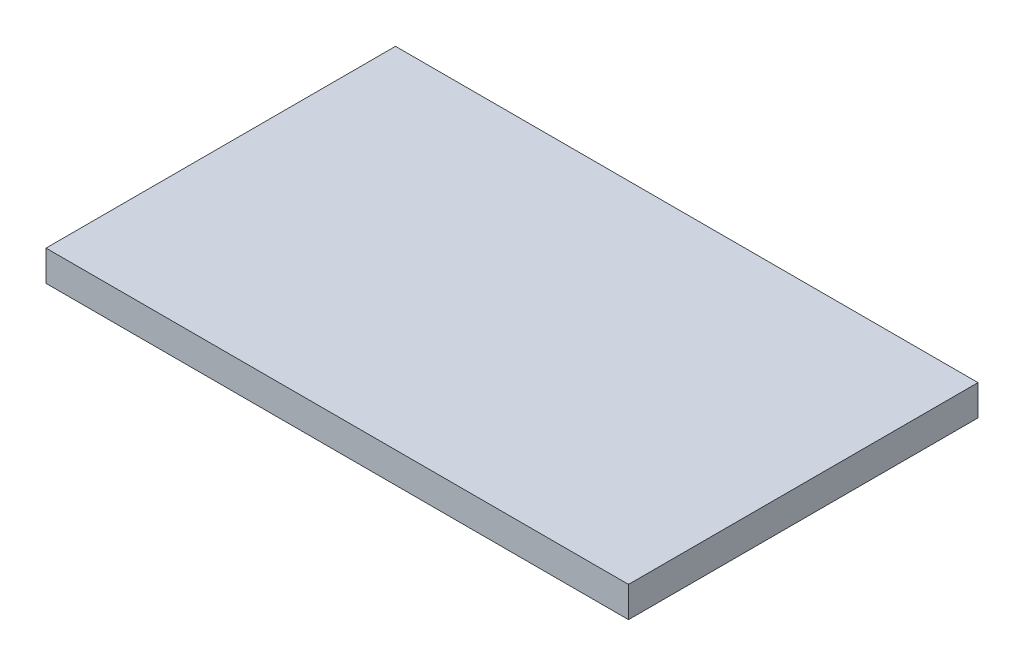
SolidWorks part; units mm, degrees
ref_plane "Front" through (0, 0, 0) normal (0, 0, 1) x (1, 0, 0)
ref_plane "Top" through (0, 0, 0) normal (0, 1, 0) x (1, 0, 0)
ref_plane "Right" through (0, 0, 0) normal (1, 0, 0) x (0, 0, -1)
sketch "Sketch1" plane through (0, 0, 0) normal (0, 1, 0) x (1, 0, 0)
  line L1 (0, 0) -> (-38.1, 0)
  line L2 (0, 0) -> (0, 22.86)
  line L3 (0, 22.86) -> (-38.1, 22.86)
  line L4 (-38.1, 0) -> (-38.1, 22.86)
  dimension "D1" = 22.86
  dimension "D2" = 38.1
extrude "Boss-Extrude1" add sketch "Sketch1" along normal blind 2
